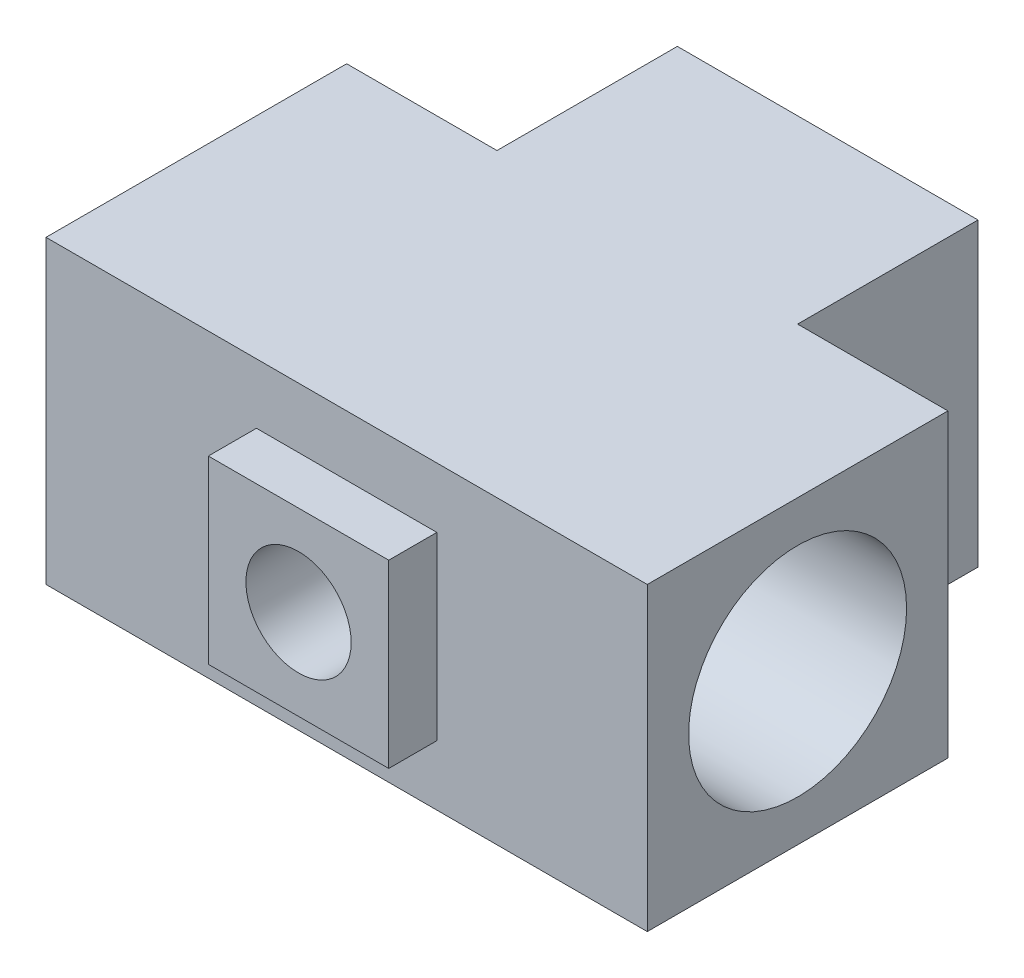
SolidWorks part; units mm, degrees
material "6061 Alloy"
ref_plane "X-Y Datum" through (0, 0, 0) normal (0, 0, 1) x (1, 0, 0)
ref_plane "X-Z Datum" through (0, 0, 0) normal (0, 1, 0) x (1, 0, 0)
ref_plane "Y-Z Datum" through (0, 0, 0) normal (1, 0, 0) x (0, 0, -1)
sketch "Sketch2" plane through (0, 0, 0) normal (0, 1, 0) x (1, 0, 0)
  line L0 (0, 15.875) -> (0, 34.925) construction
  line L1 (-31.75, -15.875) -> (31.75, -15.875)
  line L2 (-31.75, -15.875) -> (-31.75, 15.875)
  line L3 (-31.75, 15.875) -> (31.75, 15.875)
  line L4 (31.75, -15.875) -> (31.75, 15.875)
  line L5 (-31.75, -15.875) -> (31.75, 15.875) construction
  line L6 (-31.75, 15.875) -> (31.75, -15.875) construction
  line L7 (15.875, 15.875) -> (15.875, 34.925)
  line L8 (-15.875, 15.875) -> (-15.875, 34.925)
  line L9 (-15.875, 34.925) -> (15.875, 34.925)
  point P0 (0, 0)
  dimension "D1" = 31.75
  dimension "D2" = 63.5
  dimension "D5" = 19.05
  dimension "D3" = 31.75
extrude "Boss-Extrude1" add sketch "Sketch2" along normal blind 31.75 contours L1 L4 L3 L2 | L9 L8 L3 L7
hole_wizard "29/32 (0.90625) Diameter Hole1" positions "Sketch7" profile "Sketch6" hole size "29/32" standard "ANSI Inch" end condition through all
sketch "Sketch7" plane through (31.75, 0, 0) normal (1, 0, 0) x (0, 0, -1)
  line L0 (-15.875, 31.75) -> (15.875, 0)
  point P0 (0, 15.875)
sketch "Sketch6" plane through (31.75, 15.875, 0) normal (0, 1, 0) x (0, 0, -1)
  line L0 (0, 0) -> (0, 63.5)
  line L1 (0, 63.5) -> (11.5094, 63.5)
  line L2 (11.5094, 63.5) -> (11.5094, 0)
  line L5 (11.5094, 0) -> (0, 0)
  line L11 (0, -6.35) -> (0, 107.95) construction
  dimension "Thru Hole Dia." = 23.0187
  dimension "Thru Hole Depth" = 63.5
hole_wizard "29/32 (0.90625) Diameter Hole2" positions "Sketch8" profile "Sketch9" hole size "29/32" standard "ANSI Inch"
sketch "Sketch8" plane through (0, 0, -34.925) normal (0, 0, -1) x (-1, 0, 0)
  line L0 (-15.875, 31.75) -> (15.875, 0)
  point P0 (0, 15.875)
sketch "Sketch9" plane through (0, 15.875, -34.925) normal (1, 0, 0) x (0, 1, 0)
  line L0 (0, 0) -> (0, 41.2055)
  line L1 (0, 41.2055) -> (11.5094, 34.29)
  line L2 (11.5094, 34.29) -> (11.5094, 0)
  line L5 (11.5094, 0) -> (0, 0)
  line L10 (0, 41.2055) -> (-11.5094, 34.29) construction
  line L11 (0, -6.35) -> (0, 107.95) construction
  dimension "Hole Dia." = 23.0187
  dimension "Hole Depth" = 34.29
  dimension "Drill Angle" = 118
sketch "Sketch10" plane through (0, 0, 15.875) normal (0, 0, 1) x (1, 0, 0)
  line L0 (-31.75, 31.75) -> (31.75, 0)
  line L2 (-9.525, 6.35) -> (9.525, 6.35)
  line L3 (-9.525, 6.35) -> (-9.525, 25.4)
  line L4 (-9.525, 25.4) -> (9.525, 25.4)
  line L5 (9.525, 6.35) -> (9.525, 25.4)
  line L6 (-9.525, 6.35) -> (9.525, 25.4) construction
  line L7 (-9.525, 25.4) -> (9.525, 6.35) construction
  point P4 (0, 15.875)
  dimension "D1" = 19.05
  dimension "D2" = 19.05
extrude "Boss-Extrude2" add sketch "Sketch10" along normal blind 5.08 contours L2 L5 L0 L3 | L0 L5 L4 L3
hole_wizard "7/16 (0.4375) Diameter Hole1" positions "Sketch11" profile "Sketch12" hole size "7/16" standard "ANSI Inch"
sketch "Sketch11" plane through (0, 0, 20.955) normal (0, 0, 1) x (1, 0, 0)
  line L0 (-9.525, 25.4) -> (9.525, 6.35)
  point P0 (0, 15.875)
sketch "Sketch12" plane through (0, 15.875, 20.955) normal (1, 0, 0) x (0, -1, 0)
  line L0 (0, 0) -> (0, 28.7385)
  line L1 (0, 28.7385) -> (5.5562, 25.4)
  line L2 (5.5562, 25.4) -> (5.5562, 0)
  line L5 (5.5562, 0) -> (0, 0)
  line L10 (0, 28.7385) -> (-5.5563, 25.4) construction
  line L11 (0, -6.35) -> (0, 107.95) construction
  dimension "Hole Dia." = 11.1125
  dimension "Hole Depth" = 25.4
  dimension "Drill Angle" = 118
fillet "Fillet1" [suppressed] radius 3.302
thread "Thread1" [suppressed] pitch 1.8143 start angle 0, offset 0, length 0, pitch 1.8143, diameter 23.4158
ref_plane "Plane1" through (31.75, 15.875, 11.7079) normal (0, -1, 0) x (0, 0, 1)
sketch "Thread Profile1" plane through (31.75, 15.875, 11.7079) normal (0, -1, 0) x (0, 0, 1)
  line L0 (0, 0) -> (0, 1.8143) construction
  line L1 (0, 0) -> (0.982, 0.567)
  line L2 (0.982, 0.567) -> (0.982, 0.7937)
  line L3 (0.982, 0.7937) -> (0, 1.3607)
  line L4 (0.982, 0.6804) -> (0, 0.6804) construction
  line L11 (0, 0) -> (0, 1.3607)
  point P2 (0, 0)
  dimension "Pitch" = 1.8143
  dimension "Profile_Angle" = 60
  dimension "Profile_Land" = 0.2268
  dimension "Profile_Height" = 0.982
thread "Thread2" [suppressed] pitch 1.8143 start angle 0, offset 0, length 0, pitch 1.8143, diameter 23.4158
ref_plane "Plane2" through (-31.75, 15.875, -11.7079) normal (0, -1, 0) x (0, 0, -1)
sketch "Thread Profile2" plane through (-31.75, 15.875, -11.7079) normal (0, -1, 0) x (0, 0, -1)
  line L0 (0, 0) -> (0, 1.8143) construction
  line L1 (0, 0) -> (0.982, 0.567)
  line L2 (0.982, 0.567) -> (0.982, 0.7937)
  line L3 (0.982, 0.7937) -> (0, 1.3607)
  line L4 (0.982, 0.6804) -> (0, 0.6804) construction
  line L11 (0, 0) -> (0, 1.3607)
  point P2 (0, 0)
  dimension "Pitch" = 1.8143
  dimension "Profile_Angle" = 60
  dimension "Profile_Land" = 0.2268
  dimension "Profile_Height" = 0.982
thread "Thread3" [suppressed] pitch 1.8143 start angle 0, offset 0, length 0, pitch 1.8143, diameter 23.4158
ref_plane "Plane3" through (11.7079, 15.875, -34.925) normal (0, -1, 0) x (1, 0, 0)
sketch "Thread Profile3" plane through (11.7079, 15.875, -34.925) normal (0, -1, 0) x (1, 0, 0)
  line L0 (0, 0) -> (0, 1.8143) construction
  line L1 (0, 0) -> (0.982, 0.567)
  line L2 (0.982, 0.567) -> (0.982, 0.7937)
  line L3 (0.982, 0.7937) -> (0, 1.3607)
  line L4 (0.982, 0.6804) -> (0, 0.6804) construction
  line L11 (0, 0) -> (0, 1.3607)
  point P2 (0, 0)
  dimension "Pitch" = 1.8143
  dimension "Profile_Angle" = 60
  dimension "Profile_Land" = 0.2268
  dimension "Profile_Height" = 0.982
thread "Thread4" [suppressed] pitch 1.8143 start angle 0, offset 0, length 0, pitch 1.8143, diameter 11.1125
ref_plane "Plane4" through (-5.5562, 15.875, 23.495) normal (0, -1, 0) x (-1, 0, 0)
sketch "Thread Profile4" plane through (-5.5562, 15.875, 23.495) normal (0, -1, 0) x (-1, 0, 0)
  line L0 (0, 0) -> (0, 1.8143) construction
  line L1 (0, 0) -> (0.982, 0.567)
  line L2 (0.982, 0.567) -> (0.982, 0.7937)
  line L3 (0.982, 0.7937) -> (0, 1.3607)
  line L4 (0.982, 0.6804) -> (0, 0.6804) construction
  line L11 (0, 0) -> (0, 1.3607)
  point P2 (0, 0)
  dimension "Pitch" = 1.8143
  dimension "Profile_Angle" = 60
  dimension "Profile_Land" = 0.2268
  dimension "Profile_Height" = 0.982
